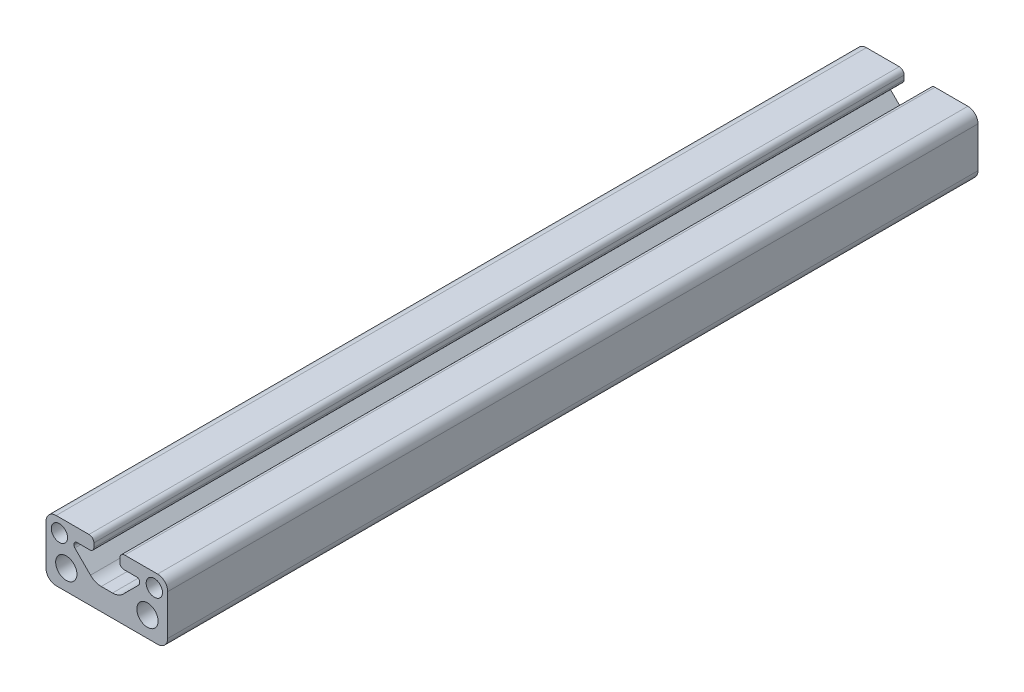
SolidWorks part; units mm, degrees
ref_plane "Front" through (0, 0, 0) normal (0, 0, 1) x (1, 0, 0)
ref_plane "Top" through (0, 0, 0) normal (0, 1, 0) x (1, 0, 0)
ref_plane "Right" through (0, 0, 0) normal (1, 0, 0) x (0, 0, -1)
sketch "Sketch2" plane through (0, 0, 0) normal (0, 0, 1) x (1, 0, 0)
  line L28 (-10.287, 4.2554) -> (-10.287, 4.572)
  line L29 (-9.398, 5.461) -> (-5.334, 5.461)
  line L30 (-4.064, 6.731) -> (-4.064, 8.001)
  line L31 (-5.588, 9.525) -> (-15.875, 9.525)
  line L32 (-19.05, 6.35) -> (-19.05, -6.35)
  line L33 (-15.875, -9.525) -> (15.875, -9.525)
  line L34 (19.05, -6.35) -> (19.05, 6.35)
  line L35 (15.875, 9.525) -> (5.588, 9.525)
  line L36 (4.064, 8.001) -> (4.064, 6.731)
  line L37 (5.334, 5.461) -> (9.398, 5.461)
  line L38 (10.287, 4.572) -> (10.287, 4.2554)
  line L39 (10.0266, 3.6267) -> (5.1241, -1.2758)
  line L40 (1.7654, -2.667) -> (-1.7654, -2.667)
  line L41 (-5.1241, -1.2758) -> (-10.0266, 3.6267)
  circle A4 centre (-14.8488, 5.2764) radius 2.5527
  circle A5 centre (-12.7, -3.175) radius 3.3274
  circle A6 centre (12.7, -3.175) radius 3.3274
  circle A7 centre (14.8488, 5.2764) radius 2.5527
  arc A28 (-10.287, 4.2554) -> (-10.0266, 3.6267) centre (-9.398, 4.2554) ccw
  arc A29 (-9.398, 5.461) -> (-10.287, 4.572) centre (-9.398, 4.572) ccw
  arc A30 (-5.334, 5.461) -> (-4.064, 6.731) centre (-5.334, 6.731) ccw
  arc A31 (-4.064, 8.001) -> (-5.588, 9.525) centre (-5.588, 8.001) ccw
  arc A32 (-15.875, 9.525) -> (-19.05, 6.35) centre (-15.875, 6.35) ccw
  arc A33 (-19.05, -6.35) -> (-15.875, -9.525) centre (-15.875, -6.35) ccw
  arc A34 (15.875, -9.525) -> (19.05, -6.35) centre (15.875, -6.35) ccw
  arc A35 (19.05, 6.35) -> (15.875, 9.525) centre (15.875, 6.35) ccw
  arc A36 (5.588, 9.525) -> (4.064, 8.001) centre (5.588, 8.001) ccw
  arc A37 (4.064, 6.731) -> (5.334, 5.461) centre (5.334, 6.731) ccw
  arc A38 (10.287, 4.572) -> (9.398, 5.461) centre (9.398, 4.572) ccw
  arc A39 (10.0266, 3.6267) -> (10.287, 4.2554) centre (9.398, 4.2554) ccw
  arc A40 (1.7654, -2.667) -> (5.1241, -1.2758) centre (1.7654, 2.0828) ccw
  arc A41 (-5.1241, -1.2758) -> (-1.7654, -2.667) centre (-1.7654, 2.0828) ccw
extrude "Boss-Extrude1" add sketch "Sketch2" along normal mid plane 253.57
